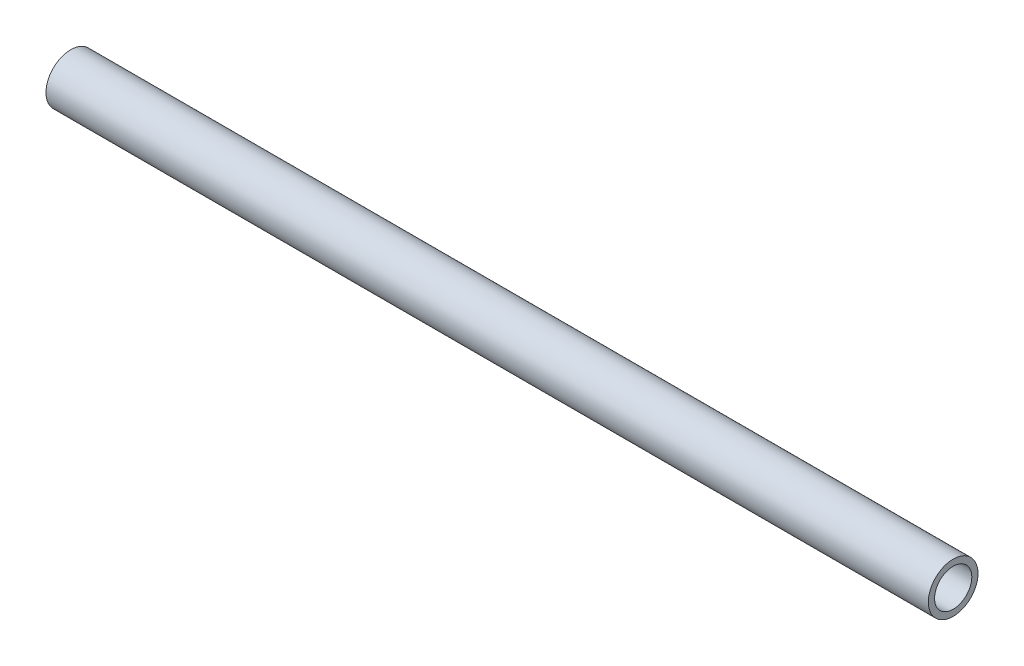
SolidWorks part; units mm, degrees
ref_plane "Front Plane" through (0, 0, 0) normal (0, 0, 1) x (1, 0, 0)
ref_plane "Top Plane" through (0, 0, 0) normal (0, 1, 0) x (1, 0, 0)
ref_plane "Right Plane" through (0, 0, 0) normal (1, 0, 0) x (0, 0, -1)
sketch "Sketch2" plane through (0, 0, 0) normal (1, 0, 0) x (0, 0, -1)
  circle A0 centre (0, 0) radius 0.5
  circle A1 centre (0, 0) radius 0.375
  dimension "D1" = 1
  dimension "D2" = 0.75
extrude "Boss-Extrude1" add sketch "Sketch2" along normal blind 17.77
